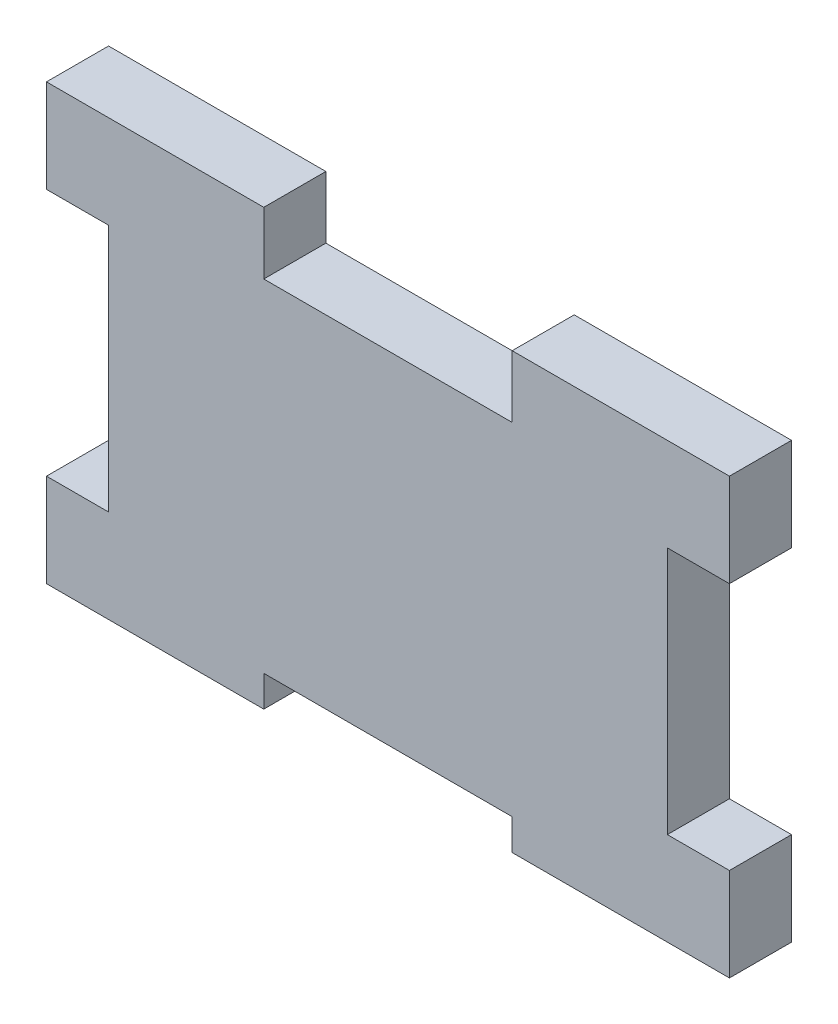
SolidWorks part; units mm, degrees
ref_plane "Front Plane" through (0, 0, 0) normal (0, 0, 1) x (1, 0, 0)
ref_plane "Top Plane" through (0, 0, 0) normal (0, 1, 0) x (1, 0, 0)
ref_plane "Right Plane" through (0, 0, 0) normal (1, 0, 0) x (0, 0, -1)
sketch "Sketch2" plane through (0, 0, 0) normal (0, 0, 1) x (1, 0, 0)
  line L0 (-10, 50) -> (-10, 65)
  line L1 (0, 0) -> (90, 0)
  line L2 (0, 0) -> (0, 55)
  line L3 (0, 55) -> (90, 55)
  line L4 (90, 0) -> (90, 55)
  line L5 (0, 50) -> (-10, 50)
  line L6 (0, 50) -> (0, 10)
  line L7 (0, 10) -> (-10, 10)
  line L8 (-10, 50) -> (-10, 10)
  line L9 (25, 55) -> (65, 55)
  line L10 (25, 55) -> (25, 65)
  line L11 (25, 65) -> (65, 65)
  line L12 (65, 55) -> (65, 65)
  line L13 (90, 50) -> (100, 50)
  line L14 (90, 50) -> (90, 10)
  line L15 (90, 10) -> (100, 10)
  line L16 (100, 50) -> (100, 10)
  line L17 (65, 0) -> (25, 0)
  line L18 (65, 0) -> (65, -5)
  line L19 (65, -5) -> (25, -5)
  line L20 (25, 0) -> (25, -5)
  line L21 (-10, 65) -> (25, 65)
  line L22 (65, 65) -> (100, 65)
  line L23 (100, 65) -> (100, 50)
  line L24 (100, 10) -> (100, -5)
  line L25 (100, -5) -> (65, -5)
  line L26 (25, -5) -> (-10, -5)
  line L27 (-10, -5) -> (-10, 10)
  point P21 (45, 65)
  point P22 (45, 55)
  point P23 (45, -5)
  dimension "D1" = 90
  dimension "D2" = 55
  dimension "D3" = 10
  dimension "D4" = 5
  dimension "D5" = 10
  dimension "D6" = 10
  dimension "D7" = 40
  dimension "D8" = 40
  dimension "D9" = 40
  dimension "D10" = 40
  dimension "D11" = 15
  dimension "D12" = 15
extrude "Boss-Extrude1" add sketch "Sketch2" along normal blind 10 contours L21 L0 L5 L2 L3 L10 | L23 L22 L12 L3 L4 L13 | L1 L4 L3 L2 | L27 L26 L20 L1 L2 L7 | L25 L24 L15 L4 L1 L18
